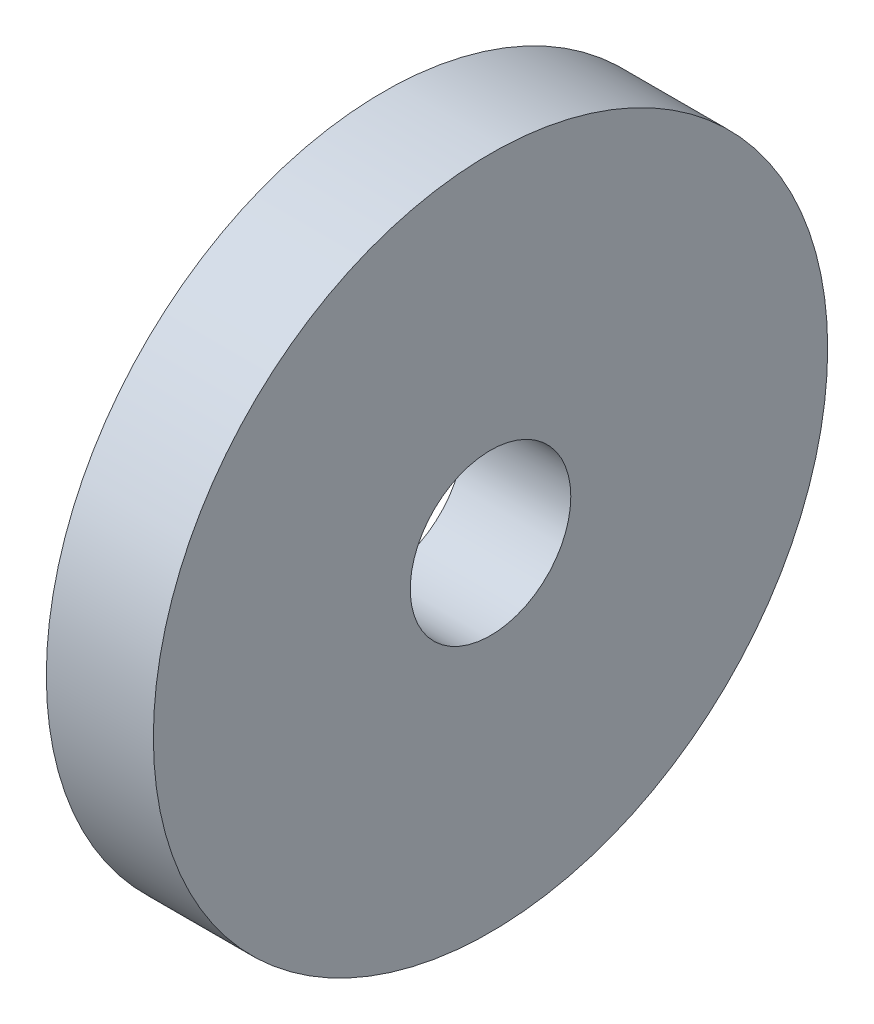
SolidWorks part; units mm, degrees
material "Silicon Rubber"
ref_plane "Front Plane" through (0, 0, 0) normal (0, 0, 1) x (1, 0, 0)
ref_plane "Top Plane" through (0, 0, 0) normal (0, 1, 0) x (1, 0, 0)
ref_plane "Right Plane" through (0, 0, 0) normal (1, 0, 0) x (0, 0, -1)
sketch "Sketch1" plane through (0, 0, 0) normal (1, 0, 0) x (0, 0, -1)
  circle A0 centre (0, 0) radius 6.3
  circle A1 centre (0, 0) radius 1.5
  dimension "D1" = 12.6
  dimension "D2" = 3
extrude "Boss-Extrude1" add sketch "Sketch1" along normal blind 2
